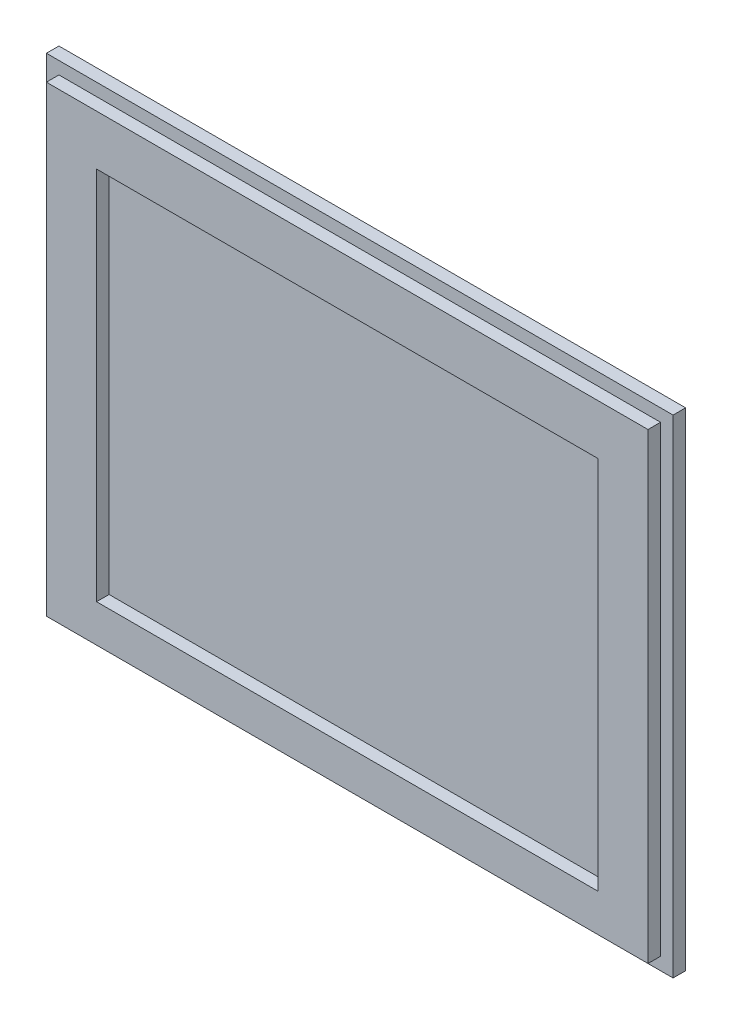
SolidWorks part; units mm, degrees
ref_plane "Ebene vorne" through (0, 0, 0) normal (0, 0, 1) x (1, 0, 0)
ref_plane "Ebene oben" through (0, 0, 0) normal (0, 1, 0) x (1, 0, 0)
ref_plane "Ebene rechts" through (0, 0, 0) normal (1, 0, 0) x (0, 0, -1)
sketch "Skizze1" plane through (0, 0, 0) normal (0, 0, 1) x (1, 0, 0)
  line L0 (-130.2667, -95.4528) -> (119.7333, -95.4528)
  line L1 (-130.2667, -95.4528) -> (-130.2667, 99.0472)
  line L2 (-130.2667, 99.0472) -> (119.7333, 99.0472)
  line L3 (119.7333, -95.4528) -> (119.7333, 99.0472)
  line L4 (-130.2667, -95.4528) -> (119.7333, 99.0472) construction
  line L5 (-130.2667, 99.0472) -> (119.7333, -95.4528) construction
  point P0 (-5.2667, 1.7972)
  dimension "D1" = 194.5
  dimension "D2" = 250
extrude "Aufsatz-Linear austragen1" add sketch "Skizze1" along normal blind 5
sketch "Skizze2" plane through (0, 0, 5) normal (0, 0, 1) x (1, 0, 0)
  line L0 (-125.2667, 94.0472) -> (114.7333, 94.0472)
  line L1 (-125.2667, 94.0472) -> (-125.2667, -90.4528)
  line L2 (114.7333, 94.0472) -> (114.7333, -90.4528)
  line L3 (-125.2667, -90.4528) -> (114.7333, -90.4528)
  line L4 (94.7333, -75.4528) -> (-105.2667, -75.4528)
  line L5 (94.7333, -75.4528) -> (94.7333, 74.0472)
  line L6 (94.7333, 74.0472) -> (-105.2667, 74.0472)
  line L7 (-105.2667, -75.4528) -> (-105.2667, 74.0472)
  line L8 (94.7333, -75.4528) -> (-105.2667, 74.0472) construction
  line L9 (94.7333, 74.0472) -> (-105.2667, -75.4528) construction
  line L10 (-130.2667, 99.0472) -> (-130.2667, -95.4528) construction
  line L11 (119.7333, 99.0472) -> (-130.2667, 99.0472) construction
  line L12 (119.7333, -95.4528) -> (119.7333, 99.0472) construction
  line L13 (-130.2667, -95.4528) -> (119.7333, -95.4528) construction
  point P0 (-5.2667, -0.7028)
  dimension "D1" = 20
  dimension "D2" = 20
  dimension "D3" = 5
  dimension "D4" = 5
  dimension "D5" = 5
  dimension "D6" = 5
  dimension "D7" = 20
  dimension "D8" = 20
extrude "Aufsatz-Linear austragen2" add sketch "Skizze2" along normal blind 5
